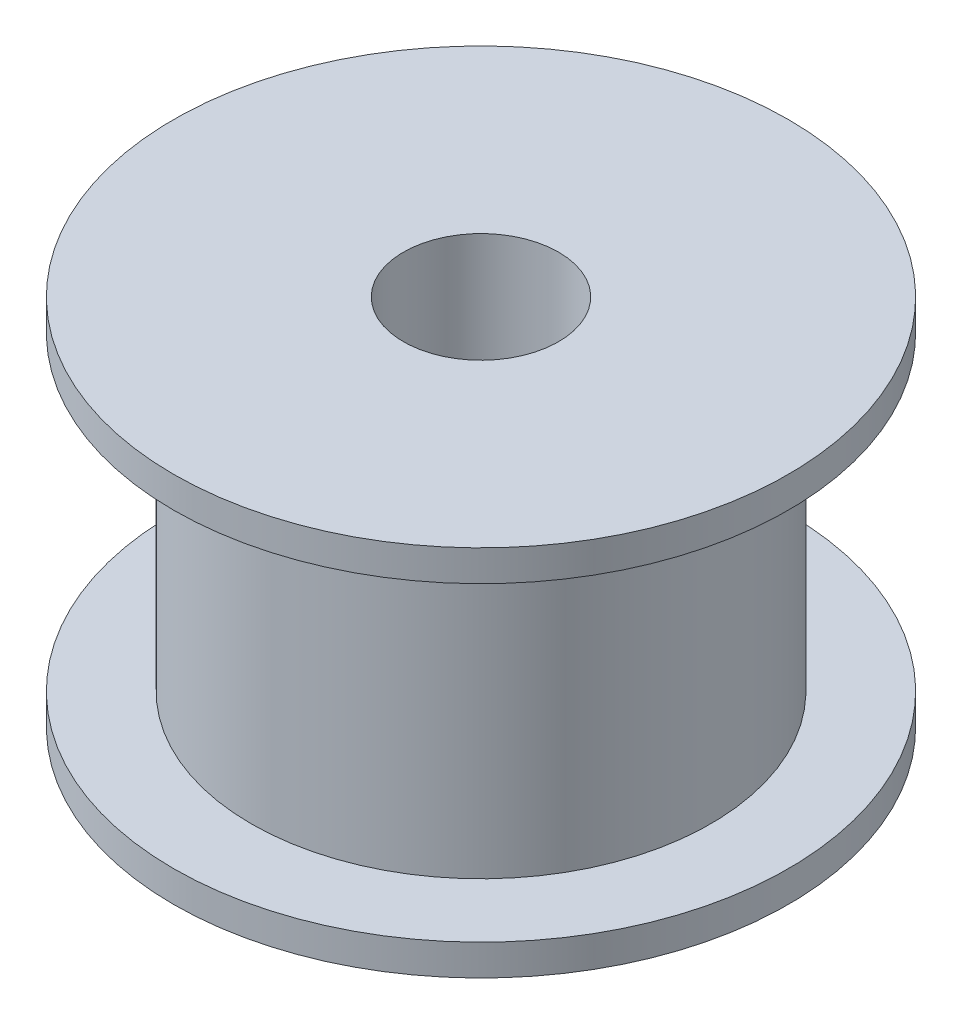
SolidWorks part; units mm, degrees
ref_plane "前视基准面" through (0, 0, 0) normal (0, 0, 1) x (1, 0, 0)
ref_plane "上视基准面" through (0, 0, 0) normal (0, 1, 0) x (1, 0, 0)
ref_plane "右视基准面" through (0, 0, 0) normal (1, 0, 0) x (0, 0, -1)
sketch "草图2" plane through (0, 0, 0) normal (0, 0, 1) x (1, 0, 0)
  line L1 (9.9, -6) -> (0, -6)
  line L2 (9.9, -6) -> (9.9, 6)
  line L3 (9.9, 6) -> (0, 6)
  line L4 (0, -6) -> (0, 6)
  line L5 (9.9, -6) -> (0, 6) construction
  line L6 (9.9, 6) -> (0, -6) construction
  line L7 (7.4, -5) -> (0, -5)
  line L8 (7.4, -5) -> (7.4, 5)
  line L9 (7.4, 5) -> (0, 5)
  line L10 (0, -5) -> (0, 5)
  line L11 (7.4, -5) -> (0, 5) construction
  line L12 (7.4, 5) -> (0, -5) construction
  line L13 (7.4, 5) -> (9.9, 5)
  line L14 (7.4, 5) -> (7.4, -5)
  line L15 (7.4, -5) -> (9.9, -5)
  line L16 (9.9, 5) -> (9.9, -5)
  line L17 (0, 6) -> (2.5, 6)
  line L18 (0, 6) -> (0, -6)
  line L19 (0, -6) -> (2.5, -6)
  line L20 (2.5, 6) -> (2.5, -6)
  point P0 (4.95, 0)
  point P5 (3.7, 0)
  dimension "D1" = 9.9
  dimension "D2" = 12
  dimension "D3" = 10
  dimension "D4" = 7.4
  dimension "D5" = 2.5
revolve "旋转1" add sketch "草图2" angle 360 about L4
